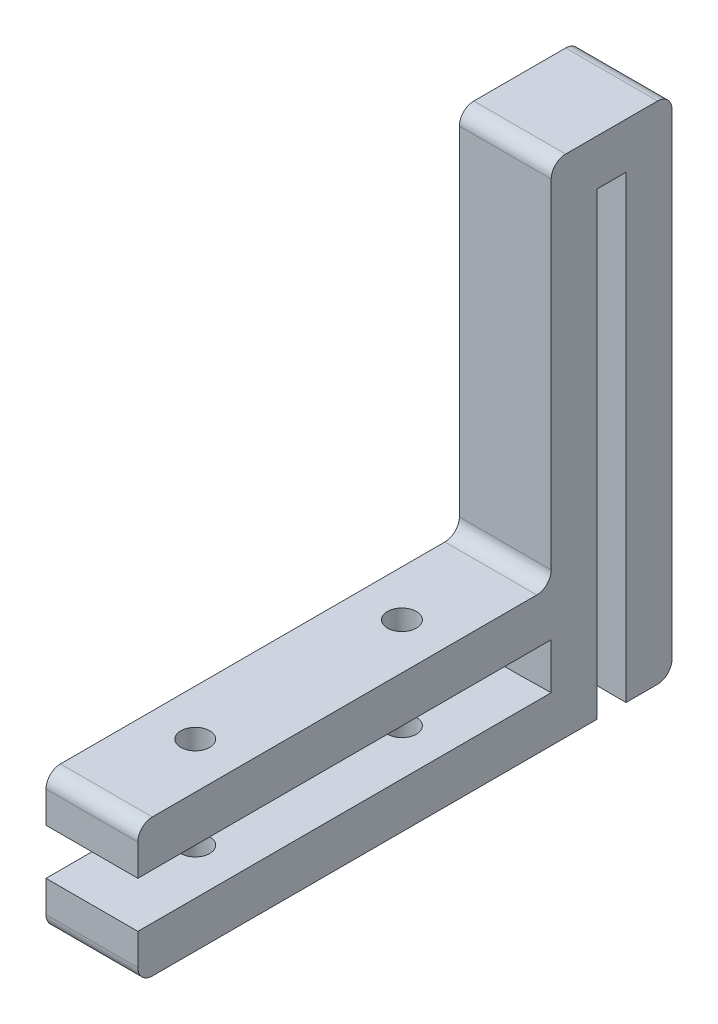
SolidWorks part; units mm, degrees
ref_plane "Front Plane" through (0, 0, 0) normal (0, 0, 1) x (1, 0, 0)
ref_plane "Top Plane" through (0, 0, 0) normal (0, 1, 0) x (1, 0, 0)
ref_plane "Right Plane" through (0, 0, 0) normal (1, 0, 0) x (0, 0, -1)
sketch "Sketch1" plane through (0, 0, 0) normal (0, 1, 0) x (1, 0, 0)
  line L1 (0, 0) -> (12.7, 0)
  line L2 (0, 0) -> (0, 63.5)
  line L3 (0, 63.5) -> (12.7, 63.5)
  line L4 (12.7, 0) -> (12.7, 63.5)
  dimension "D1" = 63.5
  dimension "D2" = 12.7
extrude "Boss-Extrude1" add sketch "Sketch1" along normal blind 6.35
sketch "Sketch2" plane through (0, 6.35, 0) normal (0, 1, 0) x (1, 0, 0)
  line L0 (12.7, 0) -> (12.7, 63.5) construction
  line L1 (0, 63.5) -> (12.7, 63.5)
  line L2 (0, 63.5) -> (0, 57.15)
  line L3 (0, 57.15) -> (12.7, 57.15)
  line L4 (12.7, 63.5) -> (12.7, 57.15)
  dimension "D1" = 6.35
extrude "Boss-Extrude2" add sketch "Sketch2" along normal blind 6.35
sketch "Sketch3" plane through (0, 12.7, 0) normal (0, 1, 0) x (1, 0, 0)
  line L1 (0, 63.5) -> (12.7, 63.5)
  line L2 (0, 63.5) -> (0, 0)
  line L3 (0, 0) -> (12.7, 0)
  line L4 (12.7, 63.5) -> (12.7, 0)
extrude "Boss-Extrude3" add sketch "Sketch3" along normal blind 6.35
sketch "Sketch4" plane through (0, 19.05, 0) normal (0, 1, 0) x (1, 0, 0)
  line L0 (12.7, 0) -> (12.7, 63.5) construction
  line L1 (0, 63.5) -> (12.7, 63.5)
  line L2 (0, 63.5) -> (0, 57.15)
  line L3 (0, 57.15) -> (12.7, 57.15)
  line L4 (12.7, 63.5) -> (12.7, 57.15)
  dimension "D1" = 6.35
extrude "Boss-Extrude4" add sketch "Sketch4" along normal blind 50.8
sketch "Sketch5" plane through (0, 0, -63.5) normal (0, 0, -1) x (-1, 0, 0)
  line L0 (0, 69.85) -> (0, 0) construction
  line L1 (-12.7, 69.85) -> (0, 69.85)
  line L2 (-12.7, 69.85) -> (-12.7, 63.5)
  line L3 (-12.7, 63.5) -> (0, 63.5)
  line L4 (0, 69.85) -> (0, 63.5)
  dimension "D1" = 6.35
extrude "Boss-Extrude5" add sketch "Sketch5" along normal blind 4
sketch "Sketch6" plane through (0, 0, -67.5) normal (0, 0, -1) x (-1, 0, 0)
  line L1 (-12.7, 69.85) -> (0, 69.85)
  line L2 (-12.7, 69.85) -> (-12.7, 0)
  line L3 (-12.7, 0) -> (0, 0)
  line L4 (0, 69.85) -> (0, 0)
extrude "Boss-Extrude6" add sketch "Sketch6" along normal blind 6.35
sketch "Sketch7" plane through (0, 6.35, 0) normal (0, 1, 0) x (1, 0, 0)
  line L0 (12.7, 57.15) -> (0, 57.15)
  arc A0 (12.7, 57.15) -> (0, 57.15) centre (6.35, 279.3093) cw
  dimension "D1" = 222.25
extrude "Boss-Extrude7" add sketch "Sketch7" along normal blind 6.35
ref_plane "Plane1" through (12.7, 19.05, -57.15) normal (0, 0, -1) x (-1, 0, 0)
sketch "Sketch9" plane through (0, 19.05, 0) normal (0, 1, 0) x (1, 0, 0)
  line L0 (6.35, 57.15) -> (6.35, 0) construction
  line L1 (0, 57.15) -> (12.7, 57.15) construction
  line L2 (0, 0) -> (12.7, 0) construction
  line L3 (0, 28.575) -> (12.7, 28.575) construction
  line L4 (12.7, 0) -> (12.7, 57.15) construction
  circle A0 centre (6.35, 42.8625) radius 2
  circle A1 centre (6.35, 14.2875) radius 2
  point P13 (6.35, 28.575)
  dimension "D2" = 4
  dimension "D1" = 14.2875
extrude "Cut-Extrude1" cut sketch "Sketch9" against normal through all
fillet "Fillet1" radius 2 5 edges at (6.35, 0, 0) (6.35, 19.05, 0) (6.35, 0, -73.85) (6.35, 69.85, -73.85) (6.35, 69.85, -57.15)
fillet "Fillet2" radius 2 1 edges at (6.35, 19.05, -57.15)
